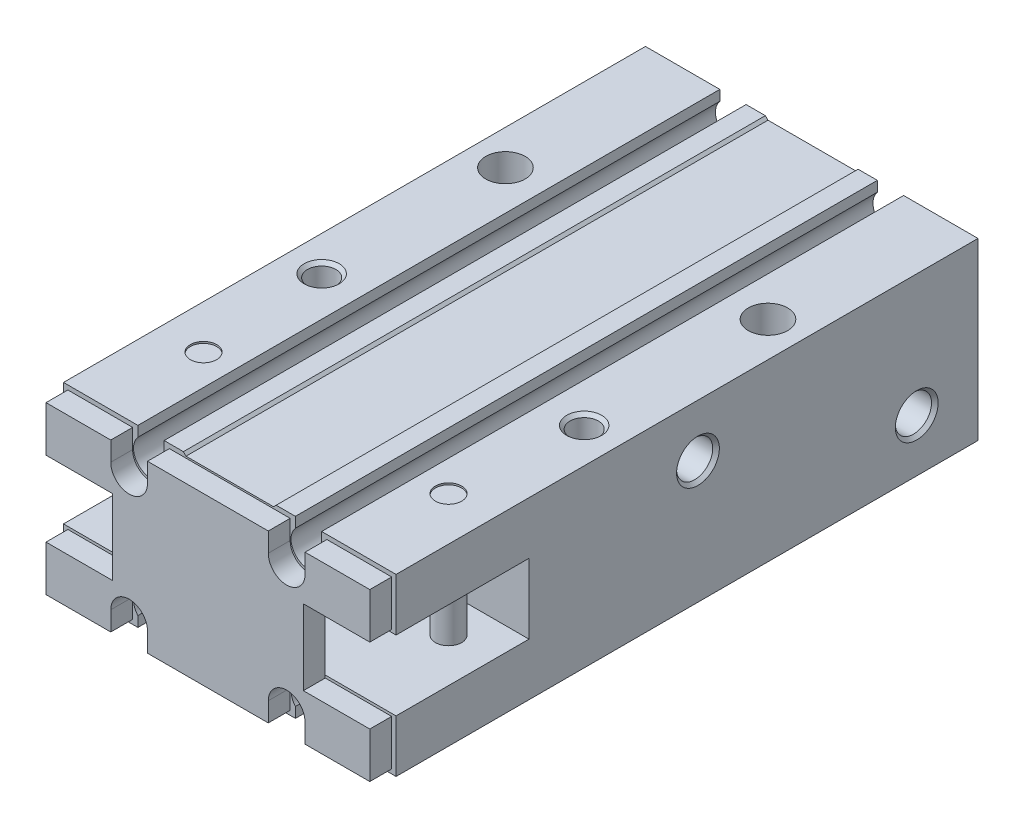
SolidWorks part; units mm, degrees
material "3.0205 (EN-AW 1200)"
ref_plane "前视基准面" through (0, 0, 0) normal (0, 0, 1) x (1, 0, 0)
ref_plane "上视基准面" through (0, 0, 0) normal (0, 1, 0) x (1, 0, 0)
ref_plane "右视基准面" through (0, 0, 0) normal (1, 0, 0) x (0, 0, -1)
ref_plane "基准面4" through (0, -9.5, 0) normal (0, -1, 0) x (1, 0, 0)
sketch "草图1" plane through (0, -9.5, 0) normal (0, -1, 0) x (1, 0, 0)
  line L0 (19, 0) -> (19, 69)
  line L1 (19, 69) -> (-19, 69)
  line L2 (-19, 69) -> (-19, 0)
  line L3 (-19, 0) -> (19, 0)
extrude "凸台-拉伸1" add sketch "草图1" against normal blind 19
sketch "草图2" plane through (0, 0, 69) normal (0, 0, 1) x (1, 0, 0)
  line L0 (-19, -4) -> (-10.91, -4)
  line L1 (-10.91, -4) -> (-10.91, 4)
  line L2 (-10.91, 4) -> (-18.5, 4)
  line L3 (-18.5, 4) -> (-18.5, 9.5)
  line L4 (-18.5, 9.5) -> (-19, 9.5)
  line L5 (-19, 9.5) -> (-19, -4)
extrude "切除-拉伸1" cut sketch "草图2" against normal blind 2.5
ref_plane "基准面5" through (0, 0, 66.5) normal (0, 0, 1) x (1, 0, 0)
ref_plane "基准面6" through (0, 0, 51.31) normal (0, 0, -1) x (-1, 0, 0)
sketch "草图4" plane through (0, 0, 51.31) normal (0, 0, -1) x (-1, 0, 0)
  line L0 (10.91, -4) -> (19, -4)
  line L1 (19, -4) -> (19, 4)
  line L2 (19, 4) -> (10.91, 4)
  line L3 (10.91, 4) -> (10.91, -4)
extrude "切除-拉伸2" cut sketch "草图4" against normal up to surface up to plane "基准面5"
sketch "草图5" plane through (-10.91, 0, 0) normal (-1, 0, 0) x (0, 0, 1)
  line L0 (66.5, 4) -> (51.31, 4)
  line L1 (51.31, 4) -> (51.31, -4)
  line L2 (51.31, -4) -> (66.5, -4)
  line L3 (66.5, -4) -> (66.5, 4)
extrude "切除-拉伸3" cut sketch "草图5" against normal blind 7.92
sketch "草图6" plane through (0, -9.5, 0) normal (0, -1, 0) x (1, 0, 0)
  line L0 (18.5, 69) -> (18.5, 66.5)
  line L1 (18.5, 66.5) -> (19, 66.5)
  line L2 (19, 66.5) -> (19, 69)
  line L3 (19, 69) -> (18.5, 69)
extrude "切除-拉伸4" cut sketch "草图6" against normal through all
sketch "草图7" plane through (0, 9.5, 0) normal (0, 1, 0) x (-1, 0, 0)
  line L0 (19, 0) -> (-19, 0)
  line L1 (-19, 0) -> (-19, 66.5)
  line L2 (-19, 66.5) -> (19, 66.5)
  line L3 (19, 66.5) -> (19, 0)
extrude "凸台-拉伸2" add sketch "草图7" along normal blind 0.5
sketch "草图8" plane through (0, -4, 0) normal (0, 1, 0) x (-1, 0, 0)
  line L0 (18.5, 66.5) -> (19, 66.5)
  line L1 (19, 66.5) -> (19, 69)
  line L2 (19, 69) -> (18.5, 69)
  line L3 (18.5, 69) -> (18.5, 66.5)
extrude "切除-拉伸5" cut sketch "草图8" against normal through all
sketch "草图9" plane through (0, -9.5, 0) normal (0, -1, 0) x (1, 0, 0)
  line L0 (19, 0) -> (-19, 0)
  line L1 (-19, 0) -> (-19, 66.5)
  line L2 (-19, 66.5) -> (19, 66.5)
  line L3 (19, 66.5) -> (19, 0)
extrude "凸台-拉伸3" add sketch "草图9" along normal blind 0.5
sketch "草图10" plane through (19, 0, 0) normal (1, 0, 0) x (0, 0, -1)
  line L0 (-66.5, -4) -> (-51.31, -4)
  line L1 (-51.31, -4) -> (-51.31, 4)
  line L2 (-51.31, 4) -> (-66.5, 4)
  line L3 (-66.5, 4) -> (-66.5, -4)
extrude "切除-拉伸6" cut sketch "草图10" against normal blind 0.5
sketch "草图11" plane through (18.5, 0, 0) normal (1, 0, 0) x (0, 0, -1)
  line L0 (-69, -4) -> (-51.31, -4)
  line L1 (-51.31, -4) -> (-51.31, 4)
  line L2 (-51.31, 4) -> (-69, 4)
  line L3 (-69, 4) -> (-69, -4)
extrude "切除-拉伸7" cut sketch "草图11" against normal blind 7.59
sketch "草图12" plane through (10.91, 0, 0) normal (1, 0, 0) x (0, 0, -1)
  line L0 (-51.31, 4) -> (-66.5, 4)
  line L1 (-66.5, 4) -> (-66.5, -4)
  line L2 (-66.5, -4) -> (-51.31, -4)
  line L3 (-51.31, -4) -> (-51.31, 4)
extrude "切除-拉伸8" cut sketch "草图12" against normal blind 7.92
ref_plane "基准面7" through (0, -4.3, 0) normal (0, -1, 0) x (1, 0, 0)
sketch "草图13" plane through (0, -4.3, 0) normal (0, -1, 0) x (1, 0, 0)
  line L0 (18.5, 66.5) -> (18.5, 69)
  line L1 (18.5, 69) -> (10.91, 69)
  line L2 (10.91, 69) -> (10.91, 66.5)
  line L3 (10.91, 66.5) -> (18.5, 66.5)
extrude "切除-拉伸9" cut sketch "草图13" against normal up to next
sketch "草图14" plane through (0, -4, 0) normal (0, 1, 0) x (-1, 0, 0)
  line L0 (18.5, 66.5) -> (18.5, 69)
  line L1 (18.5, 69) -> (10.91, 69)
  line L2 (10.91, 69) -> (10.91, 66.5)
  line L3 (10.91, 66.5) -> (18.5, 66.5)
extrude "切除-拉伸10" cut sketch "草图14" against normal blind 0.3
ref_plane "基准面8" through (0, 4.3, 0) normal (0, 1, 0) x (1, 0, 0)
sketch "草图15" plane through (0, 4.3, 0) normal (0, 1, 0) x (1, 0, 0)
  line L0 (-10.91, -66.5) -> (-18.5, -66.5)
  line L1 (-18.5, -66.5) -> (-18.5, -69)
  line L2 (-18.5, -69) -> (-10.91, -69)
  line L3 (-10.91, -69) -> (-10.91, -66.5)
extrude "切除-拉伸11" cut sketch "草图15" against normal up to next
sketch "草图16" plane through (0, 4, 0) normal (0, -1, 0) x (1, 0, 0)
  line L0 (18.5, 69) -> (10.91, 69)
  line L1 (10.91, 69) -> (10.91, 66.5)
  line L2 (10.91, 66.5) -> (18.5, 66.5)
  line L3 (18.5, 66.5) -> (18.5, 69)
extrude "切除-拉伸12" cut sketch "草图16" against normal blind 0.3
sketch "草图17" plane through (0, 0, 69) normal (0, 0, 1) x (1, 0, 0)
  line L0 (6.9, -7.3) -> (6.9, -9.5)
  line L1 (6.9, -9.5) -> (11.1, -9.5)
  line L2 (11.1, -9.5) -> (11.1, -7.3)
  arc A0 (11.1, -7.3) -> (6.9, -7.3) centre (9, -7.3) ccw
extrude "切除-拉伸13" cut sketch "草图17" against normal blind 2.5
sketch "草图18" plane through (0, 0, 69) normal (0, 0, 1) x (1, 0, 0)
  line L0 (-11.1, -7.3) -> (-11.1, -9.5)
  line L1 (-11.1, -9.5) -> (-6.9, -9.5)
  line L2 (-6.9, -9.5) -> (-6.9, -7.3)
  arc A0 (-6.9, -7.3) -> (-11.1, -7.3) centre (-9, -7.3) ccw
extrude "切除-拉伸14" cut sketch "草图18" against normal blind 2.5
sketch "草图19" plane through (0, 0, 69) normal (0, 0, 1) x (1, 0, 0)
  line L0 (-6.9, 9.5) -> (-11.1, 9.5)
  line L1 (-11.1, 9.5) -> (-11.1, 7.3)
  line L2 (-6.9, 7.3) -> (-6.9, 9.5)
  arc A0 (-11.1, 7.3) -> (-6.9, 7.3) centre (-9, 7.3) ccw
extrude "切除-拉伸15" cut sketch "草图19" against normal blind 2.5
sketch "草图20" plane through (0, 0, 69) normal (0, 0, 1) x (1, 0, 0)
  line L0 (11.1, 9.5) -> (6.9, 9.5)
  line L1 (6.9, 9.5) -> (6.9, 7.3)
  line L2 (11.1, 7.3) -> (11.1, 9.5)
  arc A0 (6.9, 7.3) -> (11.1, 7.3) centre (9, 7.3) ccw
extrude "切除-拉伸16" cut sketch "草图20" against normal blind 2.5
sketch "草图21" plane through (0, 0, 66.5) normal (0, 0, 1) x (1, 0, 0)
  line L0 (5, -10) -> (5, -9.7)
  line L1 (5, -9.7) -> (-5, -9.7)
  line L2 (-5, -9.7) -> (-5, -10)
  line L3 (-5, -10) -> (5, -10)
extrude "切除-拉伸17" cut sketch "草图21" against normal through all
sketch "草图22" plane through (0, 0, 66.5) normal (0, 0, 1) x (1, 0, 0)
  line L0 (-7.5, -10) -> (-7.5, -8.8229)
  line L1 (-10.5, -8.8229) -> (-10.5, -10)
  line L2 (-10.5, -10) -> (-7.5, -10)
  arc A0 (-7.5, -8.8229) -> (-10.5, -8.8229) centre (-9, -7.5) cw
extrude "切除-拉伸18" cut sketch "草图22" against normal through all
sketch "草图23" plane through (0, 0, 0) normal (0, 0, -1) x (-1, 0, 0)
  line L0 (-10.5, -10) -> (-7.5, -10)
  line L1 (-7.5, -10) -> (-7.5, -8.8229)
  line L2 (-10.5, -8.8229) -> (-10.5, -10)
  arc A0 (-7.5, -8.8229) -> (-10.5, -8.8229) centre (-9, -7.5) cw
extrude "切除-拉伸19" cut sketch "草图23" against normal through all
sketch "草图24" plane through (0, 0, 0) normal (0, 0, -1) x (-1, 0, 0)
  line L0 (-7.5, 10) -> (-10.5, 10)
  line L1 (-10.5, 10) -> (-10.5, 8.8229)
  line L2 (-7.5, 8.8229) -> (-7.5, 10)
  arc A0 (-10.5, 8.8229) -> (-7.5, 8.8229) centre (-9, 7.5) cw
extrude "切除-拉伸20" cut sketch "草图24" against normal through all
sketch "草图25" plane through (0, 0, 0) normal (0, 0, -1) x (-1, 0, 0)
  line L0 (5, 10) -> (-5, 10)
  line L1 (-5, 10) -> (-5, 9.7)
  line L2 (-5, 9.7) -> (5, 9.7)
  line L3 (5, 9.7) -> (5, 10)
extrude "切除-拉伸21" cut sketch "草图25" against normal blind 66.5
sketch "草图26" plane through (0, 0, 0) normal (0, 0, -1) x (-1, 0, 0)
  line L0 (10.5, 10) -> (7.5, 10)
  line L1 (7.5, 10) -> (7.5, 8.8229)
  line L2 (10.5, 8.8229) -> (10.5, 10)
  arc A0 (7.5, 8.8229) -> (10.5, 8.8229) centre (9, 7.5) cw
extrude "切除-拉伸22" cut sketch "草图26" against normal through all
sketch "草图27" plane through (0, 0, 0) normal (0, 0, -1) x (-1, 0, 0)
  line L0 (-14.5, 1.5) -> (-15.5, 1.5)
  line L1 (-15.5, -1.5) -> (-14.5, -1.5)
  arc A0 (-14.5, -1.5) -> (-14.5, 1.5) centre (-14.5, 0) ccw
  arc A1 (-15.5, 1.5) -> (-15.5, -1.5) centre (-15.5, 0) ccw
extrude "切除-拉伸23" cut sketch "草图27" against normal blind 3
draft "拔模1" type of draft neutral plane draft angle 45 faces to draft 2 face at (5, -9.85, 33.25) face at (-5, -9.85, 33.25) neutral plane through (5, -9.7, 0) neutral plane normal (0, -1, 0) parameters "D1"=45
draft "拔模2" type of draft neutral plane draft angle 45 faces to draft 2 face at (-5, 9.85, 33.25) face at (5, 9.85, 33.25) neutral plane through (5, 9.7, 66.5) neutral plane normal (0, 1, 0) parameters "D1"=45
ref_plane "基准面9" through (0, -7.5, 0) normal (0, 1, 0) x (1, 0, 0)
sketch "草图28" plane through (0, -7.5, 0) normal (0, 1, 0) x (1, 0, 0)
  line L0 (11, 0) -> (9, 0)
  line L1 (9, 0) -> (9, -66.5)
  line L2 (9, -66.5) -> (11, -66.5)
  line L3 (11, -66.5) -> (11, 0)
  line L4 (9, 0) -> (9, -66.5) construction
revolve "切除-旋转1" cut sketch "草图28" angle 360 about L4
sketch "草图29" plane through (0, -7.5, 0) normal (0, 1, 0) x (1, 0, 0)
  line L0 (-7, 0) -> (-9, 0)
  line L1 (-9, 0) -> (-9, -66.5)
  line L2 (-9, -66.5) -> (-7, -66.5)
  line L3 (-7, -66.5) -> (-7, 0)
  line L4 (-9, 0) -> (-9, -66.5) construction
revolve "切除-旋转2" cut sketch "草图29" angle 360 about L4
ref_plane "基准面10" through (0, 7.5, 0) normal (0, 1, 0) x (1, 0, 0)
sketch "草图30" plane through (0, 7.5, 0) normal (0, 1, 0) x (1, 0, 0)
  line L0 (-7, 0) -> (-9, 0)
  line L1 (-9, 0) -> (-9, -66.5)
  line L2 (-9, -66.5) -> (-7, -66.5)
  line L3 (-7, -66.5) -> (-7, 0)
  line L4 (-9, 0) -> (-9, -66.5) construction
revolve "切除-旋转3" cut sketch "草图30" angle 360 about L4
sketch "草图31" plane through (0, 7.5, 0) normal (0, 1, 0) x (1, 0, 0)
  line L0 (11, 0) -> (9, 0)
  line L1 (9, 0) -> (9, -66.5)
  line L2 (9, -66.5) -> (11, -66.5)
  line L3 (11, -66.5) -> (11, 0)
  line L4 (9, 0) -> (9, -66.5) construction
revolve "切除-旋转4" cut sketch "草图31" angle 360 about L4
ref_plane "基准面11" through (0, 0, 55.5) normal (0, 0, 1) x (1, 0, 0)
sketch "草图32" plane through (0, 0, 55.5) normal (0, 0, 1) x (1, 0, 0)
  line L0 (15.5, 4) -> (14, 4)
  line L1 (14, 4) -> (14, -4)
  line L2 (14, -4) -> (15.5, -4)
  line L3 (15.5, -4) -> (15.5, 4)
  line L4 (14, 4) -> (14, -4) construction
revolve "旋转1" add sketch "草图32" angle 360 about L4
sketch "草图33" plane through (0, 0, 55.5) normal (0, 0, 1) x (1, 0, 0)
  line L0 (-12.5, 4) -> (-14, 4)
  line L1 (-14, 4) -> (-14, -4)
  line L2 (-14, -4) -> (-12.5, -4)
  line L3 (-12.5, -4) -> (-12.5, 4)
  line L4 (-14, 4) -> (-14, -4) construction
revolve "旋转2" add sketch "草图33" angle 360 about L4
hole_wizard "Ø3.0 (3) 直径孔1" positions "草图35" profile "草图34" hole size "Ø3.0" standard "ANSI Metric"
sketch "草图35" plane through (0, 10, 0) normal (0, 1, 0) x (1, 0, 0)
  point P0 (-14, -55.5)
  point P1 (14, -55.5)
sketch "草图34" plane through (-14, 10, 55.5) normal (1, 0, 0) x (0, 0, 1)
  line L0 (0, 0) -> (0, 0.2)
  line L1 (0, 0.2) -> (1.5, 0.2)
  line L2 (1.5, 0.2) -> (1.5, 0)
  line L5 (1.5, 0) -> (0, 0)
  line L10 (0, 0.2) -> (-1.5, 0.2) construction
  line L11 (0, -6.35) -> (0, 107.95) construction
  dimension "孔直径" = 3
  dimension "孔深度" = 0.2
  dimension "导头角度" = 180
hole_wizard "M3 间隙孔1" positions "草图37" profile "草图36" hole size "M3" standard "ANSI Metric"
sketch "草图37" plane through (0, 10, 0) normal (0, 1, 0) x (1, 0, 0)
  point P0 (-15, -41)
  point P1 (15, -41)
sketch "草图36" plane through (-15, 10, 41) normal (1, 0, 0) x (0, 0, 1)
  line L0 (0, 0) -> (0, 8.9359)
  line L1 (0, 8.9359) -> (1.621, 8)
  line L2 (1.621, 8) -> (1.621, 0)
  line L5 (1.621, 0) -> (0, 0)
  line L10 (0, 8.9359) -> (-1.621, 8) construction
  line L11 (0, -6.35) -> (0, 107.95) construction
  dimension "孔直径" = 3.242
  dimension "孔深度" = 8
  dimension "导头角度" = 120
hole_wizard "M3 间隙孔2" positions "草图39" profile "草图38" hole size "M3" standard "ANSI Metric"
sketch "草图39" plane through (-19, 0, 0) normal (-1, 0, 0) x (0, 0, 1)
  point P0 (33, 6)
  point P1 (33, -6)
sketch "草图38" plane through (-19, 6, 33) normal (0, 1, 0) x (0, 0, 1)
  line L0 (0, 0) -> (0, 5.9359)
  line L1 (0, 5.9359) -> (1.621, 5)
  line L2 (1.621, 5) -> (1.621, 0)
  line L5 (1.621, 0) -> (0, 0)
  line L10 (0, 5.9359) -> (-1.621, 5) construction
  line L11 (0, -6.35) -> (0, 107.95) construction
  dimension "孔直径" = 3.242
  dimension "孔深度" = 5
  dimension "导头角度" = 120
hole_wizard "Ø3.0 (3) 直径孔2" positions "草图41" profile "草图40" hole size "Ø3.0" standard "ANSI Metric"
sketch "草图41" plane through (0, -10, 0) normal (0, -1, 0) x (-1, 0, 0)
  point P0 (-14, -55.5)
  point P1 (14, -55.5)
sketch "草图40" plane through (14, -10, 55.5) normal (1, 0, 0) x (0, 0, -1)
  line L0 (0, 0) -> (0, 0.2)
  line L1 (0, 0.2) -> (1.5, 0.2)
  line L2 (1.5, 0.2) -> (1.5, 0)
  line L5 (1.5, 0) -> (0, 0)
  line L10 (0, 0.2) -> (-1.5, 0.2) construction
  line L11 (0, -6.35) -> (0, 107.95) construction
  dimension "孔直径" = 3
  dimension "孔深度" = 0.2
  dimension "导头角度" = 180
hole_wizard "Ø4.5 (4.5) 直径孔1" positions "草图43" profile "草图42" hole size "Ø4.5" standard "ANSI Metric"
sketch "草图43" plane through (0, 10, 0) normal (0, 1, 0) x (1, 0, 0)
  point P0 (15, -20)
  point P1 (-15, -20)
sketch "草图42" plane through (15, 10, 20) normal (1, 0, 0) x (0, 0, 1)
  line L0 (0, 0) -> (0, 20)
  line L1 (0, 20) -> (2.25, 20)
  line L2 (2.25, 20) -> (2.25, 0)
  line L5 (2.25, 0) -> (0, 0)
  line L11 (0, -6.35) -> (0, 107.95) construction
  dimension "通孔孔直径" = 4.5
  dimension "通孔孔深度" = 20
hole_wizard "M3 间隙孔3" positions "草图45" profile "草图44" hole size "M3" standard "ANSI Metric"
sketch "草图45" plane through (0, -10, 0) normal (0, -1, 0) x (-1, 0, 0)
  point P0 (-15, -41)
  point P1 (15, -41)
sketch "草图44" plane through (15, -10, 41) normal (1, 0, 0) x (0, 0, -1)
  line L0 (0, 0) -> (0, 8.9359)
  line L1 (0, 8.9359) -> (1.621, 8)
  line L2 (1.621, 8) -> (1.621, 0)
  line L5 (1.621, 0) -> (0, 0)
  line L10 (0, 8.9359) -> (-1.621, 8) construction
  line L11 (0, -6.35) -> (0, 107.95) construction
  dimension "孔直径" = 3.242
  dimension "孔深度" = 8
  dimension "导头角度" = 120
hole_wizard "Ø17.0 (17) 直径孔1" positions "草图47" profile "草图46" hole size "Ø17.0" standard "ANSI Metric"
sketch "草图47" plane through (0, 0, 0) normal (0, 0, -1) x (-1, 0, 0)
  point P0 (0, 0)
sketch "草图46" plane through (0, 0, 0) normal (1, 0, 0) x (0, 1, 0)
  line L0 (0, 0) -> (0, 1.5)
  line L1 (0, 1.5) -> (8.5, 1.5)
  line L2 (8.5, 1.5) -> (8.5, 0)
  line L5 (8.5, 0) -> (0, 0)
  line L10 (0, 1.5) -> (-8.5, 1.5) construction
  line L11 (0, -6.35) -> (0, 107.95) construction
  dimension "孔直径" = 17
  dimension "孔深度" = 1.5
  dimension "导头角度" = 180
hole_wizard "M3 间隙孔4" positions "草图49" profile "草图48" hole size "M3" standard "ANSI Metric"
sketch "草图49" plane through (0, 0, 0) normal (0, 0, -1) x (-1, 0, 0)
  point P0 (15, -6)
  point P1 (-15, 6)
sketch "草图48" plane through (-15, -6, 0) normal (1, 0, 0) x (0, 1, 0)
  line L0 (0, 0) -> (0, 8.9359)
  line L1 (0, 8.9359) -> (1.621, 8)
  line L2 (1.621, 8) -> (1.621, 0)
  line L5 (1.621, 0) -> (0, 0)
  line L10 (0, 8.9359) -> (-1.621, 8) construction
  line L11 (0, -6.35) -> (0, 107.95) construction
  dimension "孔直径" = 3.242
  dimension "孔深度" = 8
  dimension "导头角度" = 120
hole_wizard "M3.5 间隙孔1" positions "草图51" profile "草图50" hole size "M3.5" standard "ANSI Metric"
sketch "草图51" plane through (19, 0, 0) normal (1, 0, 0) x (0, 0, -1)
  point P0 (-7, -4)
  point P1 (-32, 4)
sketch "草图50" plane through (19, -4, 7) normal (0, 1, 0) x (0, 0, -1)
  line L0 (0, 0) -> (0, 6.1934)
  line L1 (0, 6.1934) -> (2.067, 5)
  line L2 (2.067, 5) -> (2.067, 0)
  line L5 (2.067, 0) -> (0, 0)
  line L10 (0, 6.1934) -> (-2.067, 5) construction
  line L11 (0, -6.35) -> (0, 107.95) construction
  dimension "孔直径" = 4.134
  dimension "孔深度" = 5
  dimension "导头角度" = 120
chamfer "倒角1" distance 0.379 angle 45 10 edges at (-19, -6, 34.621) (-15, -10, 39.379) (15, -10, 39.379) (-15, 10, 42.621) (15, 10, 42.621) (19, -4, 4.933) (19, 4, 29.933) (-19, 6, 34.621) (-16.621, -6, 0) (13.379, 6, 0)
